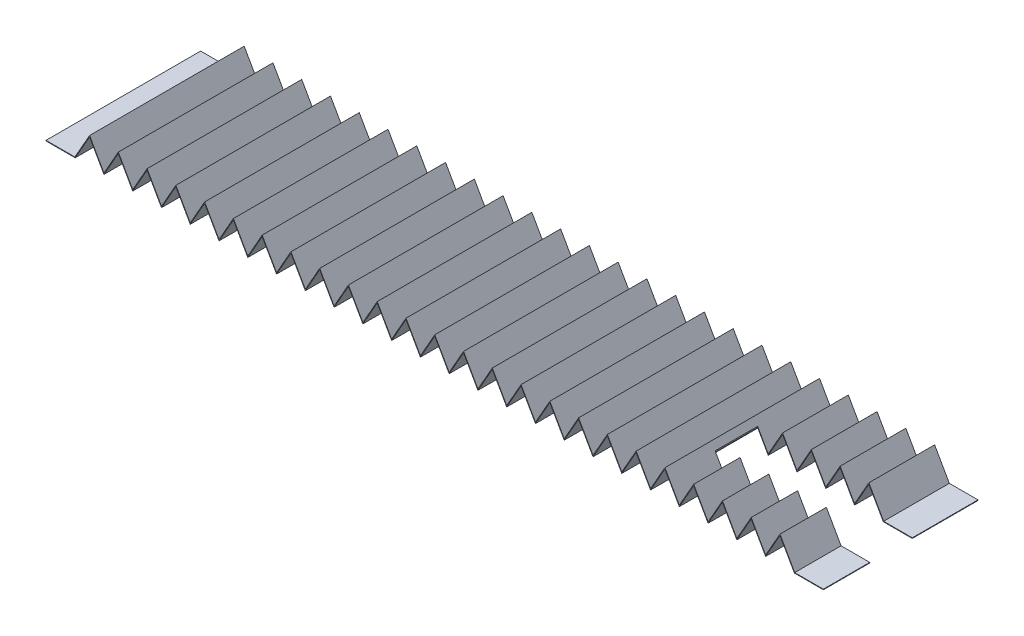
SolidWorks part; units mm, degrees
ref_plane "Front Plane" through (0, 0, 0) normal (0, 0, 1) x (1, 0, 0)
ref_plane "Top Plane" through (0, 0, 0) normal (0, 1, 0) x (1, 0, 0)
ref_plane "Right Plane" through (0, 0, 0) normal (1, 0, 0) x (0, 0, -1)
sketch "Sketch1" plane through (0, 0, 0) normal (0, 0, 1) x (1, 0, 0)
  line L0 (0, 0) -> (7.4417, 13.1389)
  line L1 (7.4417, 13.1389) -> (14.8834, 0)
  line L2 (0, 0) -> (511, 0) construction
  line L3 (14.8834, 0) -> (22.3251, 13.1389)
  line L4 (22.3251, 13.1389) -> (29.7668, 0)
  line L5 (29.7668, 0) -> (37.2085, 13.1389)
  line L6 (37.2085, 13.1389) -> (44.6502, 0)
  line L7 (44.6502, 0) -> (52.0919, 13.1389)
  line L8 (52.0919, 13.1389) -> (59.5336, 0)
  line L9 (59.5336, 0) -> (66.9753, 13.1389)
  line L10 (66.9753, 13.1389) -> (74.417, 0)
  line L11 (74.417, 0) -> (81.8587, 13.1389)
  line L12 (81.8587, 13.1389) -> (89.3004, 0)
  line L13 (89.3004, 0) -> (96.7421, 13.1389)
  line L14 (96.7421, 13.1389) -> (104.1838, 0)
  line L15 (104.1838, 0) -> (111.6255, 13.1389)
  line L16 (111.6255, 13.1389) -> (119.0672, 0)
  line L17 (119.0672, 0) -> (126.5089, 13.1389)
  line L18 (126.5089, 13.1389) -> (133.9506, 0)
  line L19 (0, 0) -> (-15.1, 0)
  line L20 (133.9506, 0) -> (141.3923, 13.1389)
  line L21 (141.3923, 13.1389) -> (148.834, 0)
  line L22 (148.834, 0) -> (156.2757, 13.1389)
  line L23 (156.2757, 13.1389) -> (163.7174, 0)
  line L24 (163.7174, 0) -> (171.1591, 13.1389)
  line L25 (171.1591, 13.1389) -> (178.6008, 0)
  line L26 (178.6008, 0) -> (186.0425, 13.1389)
  line L27 (186.0425, 13.1389) -> (193.4842, 0)
  line L28 (193.4842, 0) -> (200.9259, 13.1389)
  line L29 (200.9259, 13.1389) -> (208.3676, 0)
  line L30 (208.3676, 0) -> (215.8093, 13.1389)
  line L31 (215.8093, 13.1389) -> (223.251, 0)
  line L32 (223.251, 0) -> (230.6927, 13.1389)
  line L33 (230.6927, 13.1389) -> (238.1344, 0)
  line L34 (238.1344, 0) -> (245.5761, 13.1389)
  line L35 (245.5761, 13.1389) -> (253.0178, 0)
  line L36 (253.0178, 0) -> (260.4595, 13.1389)
  line L37 (260.4595, 13.1389) -> (267.9012, 0)
  line L38 (289.085, -119) -> (289.085, 132.963) construction
  line L39 (267.9012, 0) -> (275.3429, 13.1389)
  line L40 (275.3429, 13.1389) -> (282.7846, 0)
  line L41 (282.7846, 0) -> (290.2263, 13.1389)
  line L42 (290.2263, 13.1389) -> (297.668, 0)
  line L43 (297.668, 0) -> (305.1097, 13.1389)
  line L44 (305.1097, 13.1389) -> (312.5514, 0)
  line L45 (312.5514, 0) -> (319.9931, 13.1389)
  line L46 (319.9931, 13.1389) -> (327.4348, 0)
  line L47 (327.4348, 0) -> (334.8765, 13.1389)
  line L48 (334.8765, 13.1389) -> (342.3182, 0)
  line L49 (342.3182, 0) -> (349.7599, 13.1389)
  line L51 (349.7599, 13.1389) -> (357.2016, 0)
  line L52 (357.2016, 0) -> (364.6433, 13.1389)
  line L53 (364.6433, 13.1389) -> (372.085, 0)
  line L54 (372.085, 0) -> (387.085, 0)
  dimension "D1" = 511
  dimension "D2" = 15.1
  dimension "D3" = 15
  dimension "D4" = 14.8834
  dimension "D6" = 98
  dimension "D5" = 25
extrude "Extrude-Thin1" add sketch "Sketch1" along normal mid plane 80 thin thin type one direction reverse wall 0.3
sketch "Sketch2" plane through (0, 0, 0) normal (0, 1, 0) x (1, 0, 0)
  line L1 (307.085, -16) -> (387.085, -16)
  line L2 (307.085, -16) -> (307.085, 6)
  line L3 (307.085, 6) -> (387.085, 6)
  line L4 (387.085, -16) -> (387.085, 6)
  line L5 (307.085, -16) -> (387.085, 6) construction
  line L6 (307.085, 6) -> (387.085, -16) construction
  line L8 (387.085, -40) -> (387.085, 40) construction
  point P0 (347.085, -5)
  dimension "D1" = 80
  dimension "D2" = 22
  dimension "D3" = 5
extrude "Cut-Extrude4" cut sketch "Sketch2" against normal through all and the other way through all contours L1 L4 L3 L2
